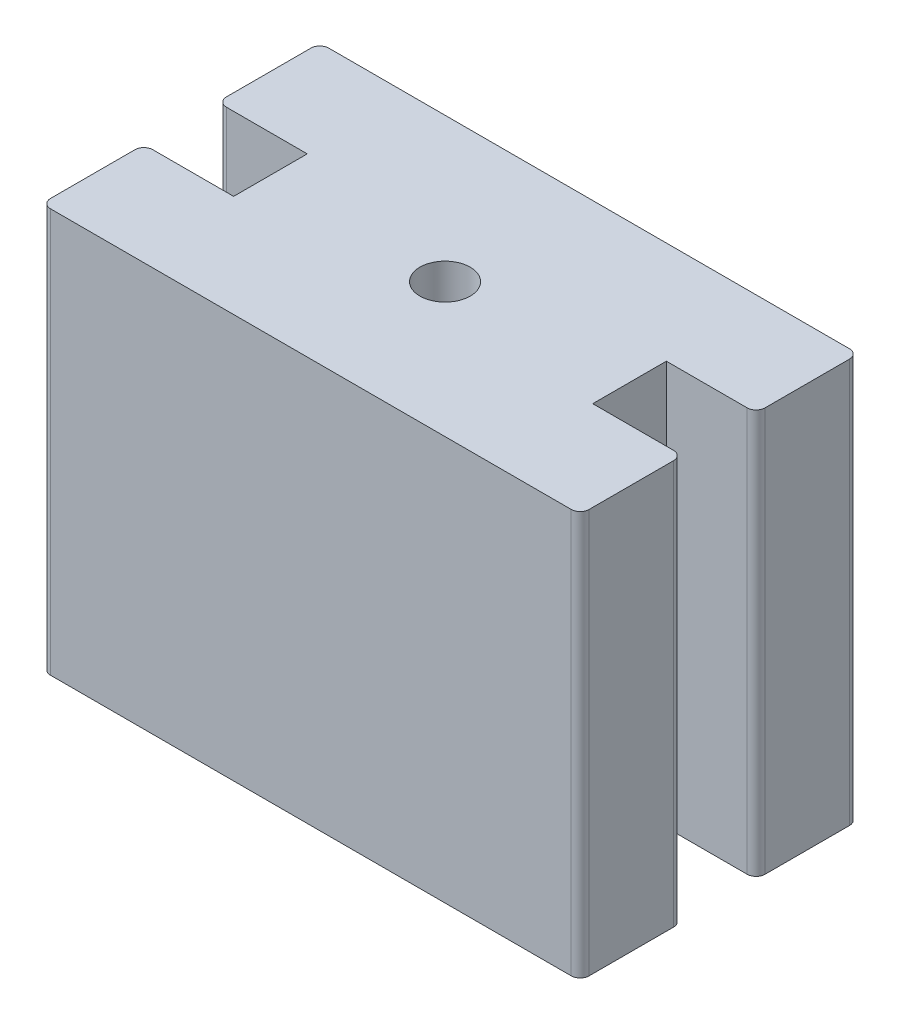
SolidWorks part; units mm, degrees
ref_plane "Front Plane" through (0, 0, 0) normal (0, 0, 1) x (1, 0, 0)
ref_plane "Top Plane" through (0, 0, 0) normal (0, 1, 0) x (1, 0, 0)
ref_plane "Right Plane" through (0, 0, 0) normal (1, 0, 0) x (0, 0, -1)
sketch "Sketch1" plane through (0, 0, 0) normal (0, 1, 0) x (1, 0, 0)
  line L0 (20, 4.65) -> (29, 4.65)
  line L1 (-20, 16.05) -> (20, 16.05)
  line L2 (-20, 4.65) -> (-20, -3.55)
  line L3 (-20, -14.95) -> (20, -14.95)
  line L4 (20, 4.65) -> (20, -3.55)
  line L7 (-29, 16.05) -> (29, 16.05)
  line L8 (-30, 15.05) -> (-30, 5.65)
  line L9 (-29, 4.65) -> (-20, 4.65)
  line L10 (30, 15.05) -> (30, 5.65)
  line L11 (-29, -14.95) -> (29, -14.95)
  line L12 (-30, -13.95) -> (-30, -4.55)
  line L13 (-29, -3.55) -> (-20, -3.55)
  line L14 (30, -13.95) -> (30, -4.55)
  line L15 (20, -3.55) -> (29, -3.55)
  arc A0 (-29, -14.95) -> (-30, -13.95) centre (-29, -13.95) cw
  arc A1 (-30, -4.55) -> (-29, -3.55) centre (-29, -4.55) cw
  arc A2 (-30, 5.65) -> (-29, 4.65) centre (-29, 5.65) ccw
  arc A3 (-29, 16.05) -> (-30, 15.05) centre (-29, 15.05) ccw
  arc A4 (29, -14.95) -> (30, -13.95) centre (29, -13.95) ccw
  arc A5 (29, -3.55) -> (30, -4.55) centre (29, -4.55) cw
  arc A6 (29, 4.65) -> (30, 5.65) centre (29, 5.65) ccw
  arc A7 (29, 16.05) -> (30, 15.05) centre (29, 15.05) cw
  circle A8 centre (0, 0) radius 2.8
  point P0 (0, 0)
  dimension "D6" = 1
  dimension "D7" = 1
  dimension "D8" = 5.6
  dimension "D1" = 40
  dimension "D2" = 31
  dimension "D3" = 8.2
  dimension "D4" = 10
  dimension "D5" = 10
extrude "Boss-Extrude1" add sketch "Sketch1" along normal blind 45 contours A7 L7 L1 A3 L8 A2 L9 L2 L13 A1 L12 A0 L11 L3 A4 L14 A5 L15 L4 L0 A6 L10 A8
